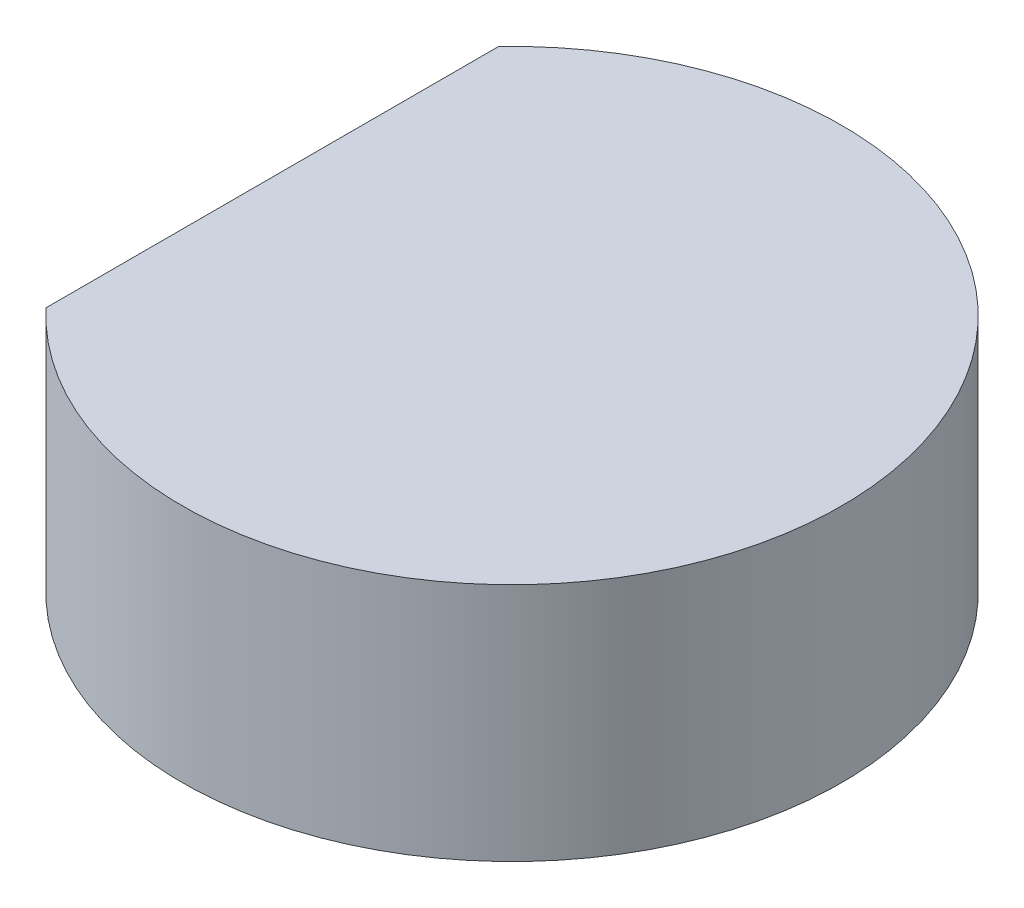
SolidWorks part; units mm, degrees
ref_plane "Front Plane" through (0, 0, 0) normal (0, 0, 1) x (1, 0, 0)
ref_plane "Top Plane" through (0, 0, 0) normal (0, 1, 0) x (1, 0, 0)
ref_plane "Right Plane" through (0, 0, 0) normal (1, 0, 0) x (0, 0, -1)
sketch "Sketch1" plane through (0, 0, 0) normal (0, 1, 0) x (1, 0, 0)
  circle A0 centre (0, 0) radius 6.985
  dimension "D1" = 13.97
extrude "Boss-Extrude1" add sketch "Sketch1" along normal blind 5.08
sketch "Sketch4" plane through (0, 5.08, 0) normal (0, 1, 0) x (1, 0, 0)
  line L0 (0, 0) -> (-6.985, 0) construction
  line L2 (-8.89, -6.35) -> (-5.08, -6.35)
  line L3 (-8.89, -6.35) -> (-8.89, 6.35)
  line L4 (-8.89, 6.35) -> (-5.08, 6.35)
  line L5 (-5.08, -6.35) -> (-5.08, 6.35)
  line L6 (-8.89, -6.35) -> (-5.08, 6.35) construction
  line L7 (-8.89, 6.35) -> (-5.08, -6.35) construction
  circle A0 centre (0, 0) radius 6.985 construction
  dimension "D1" = 3.81
  dimension "D2" = 12.7
extrude "Cut-Extrude1" cut sketch "Sketch4" against normal through all
